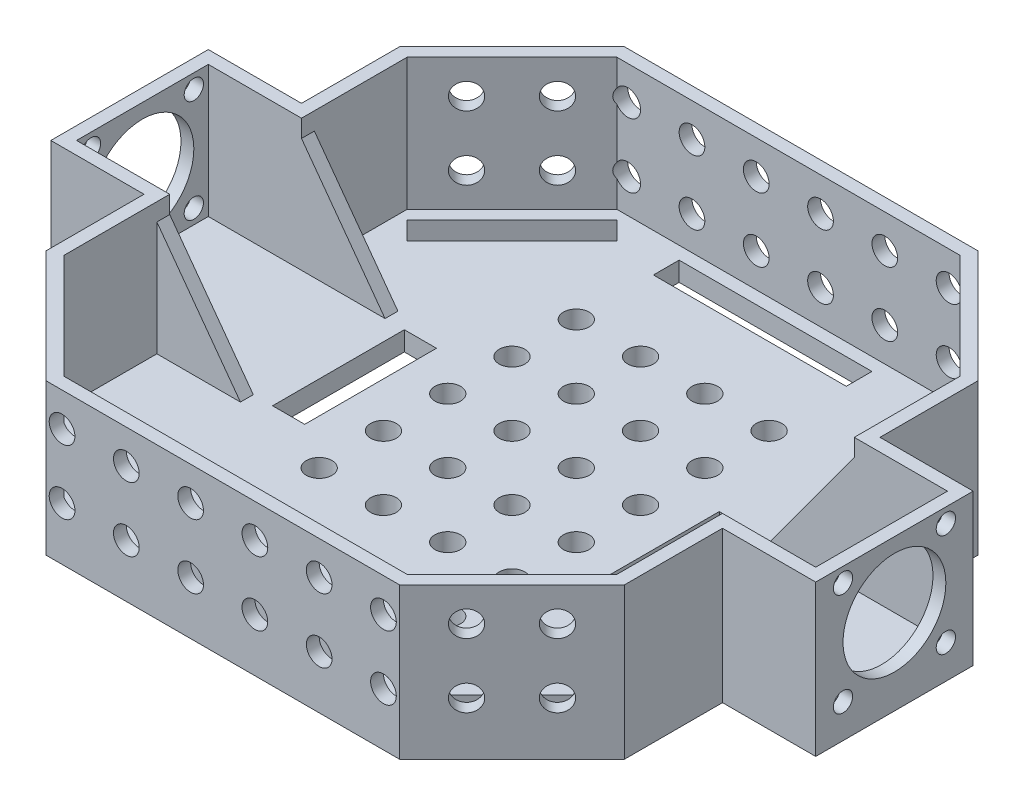
SolidWorks part; units mm, degrees
ref_plane "Front Plane" through (0, 0, 0) normal (0, 0, 1) x (1, 0, 0)
ref_plane "Top Plane" through (0, 0, 0) normal (0, 1, 0) x (1, 0, 0)
ref_plane "Right Plane" through (0, 0, 0) normal (1, 0, 0) x (0, 0, -1)
sketch "Sketch1" plane through (0, 0, 0) normal (0, 1, 0) x (1, 0, 0)
  line L1 (0, 0) -> (90, 0)
  line L2 (0, 0) -> (0, 90)
  line L3 (0, 90) -> (90, 90)
  line L4 (90, 0) -> (90, 90)
  dimension "D1" = 90
extrude "Boss-Extrude1" add sketch "Sketch1" along normal blind 3
sketch "Sketch2" plane through (0, 3, 0) normal (0, 1, 0) x (1, 0, 0)
  line L0 (0, 90) -> (0, 0) construction
  line L1 (0, 34.75) -> (-14.5, 34.75)
  line L2 (0, 34.75) -> (0, 55.25)
  line L3 (0, 55.25) -> (-14.5, 55.25)
  line L4 (-14.5, 34.75) -> (-14.5, 55.25)
  line L5 (90, 0) -> (90, 90) construction
  line L6 (90, 34.75) -> (104.5, 34.75)
  line L7 (90, 34.75) -> (90, 55.25)
  line L8 (90, 55.25) -> (104.5, 55.25)
  line L9 (104.5, 34.75) -> (104.5, 55.25)
  line L10 (-14.5, 55.25) -> (17.5, 55.25) construction
  line L11 (104.5, 55.25) -> (72.5, 55.25) construction
  point P12 (97.9626, 54.4694)
  point P13 (90, 45)
  point P14 (90, 45)
  point P15 (0, 45)
  point P16 (0, 45)
  dimension "D1" = 32
  dimension "D2" = 55
  dimension "D3" = 20.5
extrude "Boss-Extrude2" add sketch "Sketch2" against normal up to surface (3 mm away) up to face at (45, 0, -45)
sketch "Sketch3" plane through (0, 3, 0) normal (0, 1, 0) x (1, 0, 0)
  line L0 (-14.5, 34.75) -> (0, 34.75) construction
  line L1 (-14.5, 55.25) -> (-12.5, 55.25)
  line L2 (-14.5, 55.25) -> (-14.5, 34.75)
  line L3 (-14.5, 34.75) -> (-12.5, 34.75)
  line L4 (-12.5, 55.25) -> (-12.5, 34.75)
  line L5 (104.5, 55.25) -> (90, 55.25) construction
  line L6 (104.5, 34.75) -> (102.5, 34.75)
  line L7 (104.5, 34.75) -> (104.5, 55.25)
  line L8 (104.5, 55.25) -> (102.5, 55.25)
  line L9 (102.5, 34.75) -> (102.5, 55.25)
  dimension "D1" = 2
extrude "Boss-Extrude3" add sketch "Sketch3" along normal blind 20.5
sketch "Sketch4" plane through (-12.5, 0, 0) normal (1, 0, 0) x (0, 0, -1)
  line L0 (34.75, 3.25) -> (55.25, 3.25) construction
  line L1 (34.75, 23.5) -> (34.75, 3) construction
  line L2 (55.25, 23.5) -> (55.25, 3) construction
  line L3 (34.75, 3) -> (55.25, 3) construction
  line L5 (34.75, 23.5) -> (55.25, 23.5) construction
  line L6 (37, 5.25) -> (53, 5.25) construction
  line L7 (53, 5.25) -> (53, 21.25) construction
  circle A0 centre (45, 13.25) radius 8
  circle A1 centre (53, 21.25) radius 1.5
  circle A2 centre (53, 5.25) radius 1.5
  circle A3 centre (37, 21.25) radius 1.5
  circle A4 centre (37, 5.25) radius 1.5
  point P13 (45, 23.5)
  point P21 (53, 13.25)
  point P22 (48.4513, 5.25)
  point P23 (45, 5.25)
  point P24 (45, 3.25)
  point P25 (37, 5.25)
  dimension "D2" = 16
  dimension "D7" = 3
  dimension "D1" = 0.25
  dimension "D3" = 10
  dimension "D4" = 16
  dimension "D5" = 16
  dimension "D6" = 10
extrude "Cut-Extrude1" cut sketch "Sketch4" against normal through all both and the other way through all
sketch "Sketch5" plane through (0, 3, 0) normal (0, 1, 0) x (1, 0, 0)
  line L0 (-14.5, 55.25) -> (-14.5, 34.75) construction
  line L1 (2, 34.75) -> (-14.5, 34.75)
  line L2 (2, 34.75) -> (2, 32.75)
  line L3 (2, 32.75) -> (-14.5, 32.75)
  line L4 (-14.5, 34.75) -> (-14.5, 32.75)
  line L5 (-12.5, 45) -> (104.5, 45) construction
  line L6 (-12.5, 34.75) -> (-12.5, 55.25) construction
  line L7 (104.5, 34.75) -> (104.5, 55.25) construction
  line L8 (104.5, 34.75) -> (104.5, 55.25)
  line L9 (45, 0) -> (45, 90) construction
  line L10 (0, 0) -> (90, 0) construction
  line L11 (90, 90) -> (0, 90) construction
  line L12 (2, 57.25) -> (-14.5, 57.25)
  line L13 (-14.5, 55.25) -> (-14.5, 57.25)
  line L14 (2, 55.25) -> (-14.5, 55.25)
  line L15 (2, 55.25) -> (2, 57.25)
  line L16 (88, 32.75) -> (104.5, 32.75)
  line L17 (104.5, 34.75) -> (104.5, 32.75)
  line L18 (88, 34.75) -> (104.5, 34.75)
  line L19 (88, 34.75) -> (88, 32.75)
  line L20 (88, 55.25) -> (88, 57.25)
  line L21 (88, 55.25) -> (104.5, 55.25)
  line L22 (104.5, 55.25) -> (104.5, 57.25)
  line L23 (88, 57.25) -> (104.5, 57.25)
  line L24 (-12.5, 34.75) -> (0, 34.75) construction
  point P4 (2.0114, 34.6763)
  point P31 (0, 34.75)
  point P32 (0, 0)
  point P33 (86.9296, 57.25)
  dimension "D1" = 2
  dimension "D2" = 2
extrude "Boss-Extrude4" add sketch "Sketch5" against normal up to surface and the other way up to surface contours L12 L13 L14 L15 | L2 L1 L4 L3 | L20 L23 L22 L21 | L16 L17 L18 L19 up to face at (45, 0, -45) other way up to face at (103.5, 23.5, -45)
sketch "Sketch6" plane through (0, 0, -57.25) normal (0, 0, -1) x (-1, 0, 0)
  line L0 (-90, 23.5) -> (-75, 3)
  line L2 (-75, 3) -> (-90, 3)
  line L3 (-90, 3) -> (-90, 23.5)
  line L4 (0, 23.5) -> (-15, 3)
  line L5 (-15, 3) -> (0, 3)
  line L6 (0, 3) -> (0, 23.5)
  line L7 (-88, 23.5) -> (-104.5, 23.5) construction
  line L8 (-2, 23.5) -> (14.5, 23.5) construction
  point P3 (-20.5, 3)
  point P4 (-69.5, 3)
  point P10 (-20.5, 3)
  point P13 (-20.5, 3)
  point P14 (-69.5, 3)
  point P15 (-10.2777, 3)
  point P16 (-67.4871, 3)
  point P17 (-74.1327, 3)
  point P18 (-90, 23.5)
  point P21 (0, 23.5)
  dimension "D1" = 15
extrude "Boss-Extrude5" add sketch "Sketch6" against normal up to surface (24.5 mm away) up to face at (94.1667, 8.8333, -32.75)
sketch "Sketch7" plane through (0, 3, 0) normal (0, 1, 0) x (1, 0, 0)
  line L1 (102.5, 34.75) -> (-12.5, 34.75)
  line L2 (102.5, 34.75) -> (102.5, 55.25)
  line L3 (102.5, 55.25) -> (-12.5, 55.25)
  line L4 (-12.5, 34.75) -> (-12.5, 55.25)
extrude "Cut-Extrude2" cut sketch "Sketch7" along normal through all
sketch "Sketch8" plane through (0, 3, 0) normal (0, 1, 0) x (1, 0, 0)
  line L0 (15, 55.25) -> (-12.5, 55.25) construction
  line L1 (18, 55.25) -> (23, 55.25)
  line L2 (18, 55.25) -> (18, 34.75)
  line L3 (18, 34.75) -> (23, 34.75)
  line L4 (23, 55.25) -> (23, 34.75)
  line L5 (67, 55.25) -> (72, 55.25)
  line L6 (67, 55.25) -> (67, 34.75)
  line L7 (67, 34.75) -> (72, 34.75)
  line L8 (72, 55.25) -> (72, 34.75)
  line L9 (-12.5, 34.75) -> (15, 34.75) construction
  line L10 (18, 55.25) -> (15, 55.25) construction
  line L11 (72, 55.25) -> (75, 55.25) construction
  line L12 (-12.5, 34.75) -> (-12.5, 55.25) construction
  dimension "D1" = 30.5
  dimension "D2" = 5
extrude "Cut-Extrude3" cut sketch "Sketch8" against normal through all
sketch "Sketch9" plane through (0, 0, 0) normal (0, -1, 0) x (1, 0, 0)
  line L0 (17.5, 0) -> (0, -17.5)
  line L1 (0, 0) -> (90, 0) construction
  line L2 (0, -32.75) -> (0, 0) construction
  line L3 (0, -17.5) -> (0, 0)
  line L4 (0, 0) -> (17.5, 0)
  line L5 (45, 0) -> (45, -90) construction
  line L6 (90, -90) -> (0, -90) construction
  line L7 (0, -72.5) -> (17.5, -90)
  line L8 (0, -90) -> (0, -57.25) construction
  line L9 (17.5, -90) -> (0, -90)
  line L10 (0, -90) -> (0, -72.5)
  line L11 (72.5, -90) -> (90, -90)
  line L12 (90, -72.5) -> (72.5, -90)
  line L13 (90, -90) -> (90, -72.5)
  line L14 (90, -17.5) -> (90, 0)
  line L15 (72.5, 0) -> (90, -17.5)
  line L16 (90, 0) -> (72.5, 0)
  point P16 (16.3771, 0)
  point P19 (0, -12.7712)
  dimension "D1" = 17.5
extrude "Cut-Extrude4" cut sketch "Sketch9" against normal through all
sketch "Sketch10" plane through (0, 3, 0) normal (0, 1, 0) x (1, 0, 0)
  line L0 (88, 32.75) -> (88, 18.3284)
  line L1 (90, 32.75) -> (75, 32.75) construction
  line L2 (88, 18.3284) -> (71.6716, 2)
  line L3 (71.6716, 2) -> (18.3284, 2)
  line L4 (18.3284, 2) -> (2, 18.3284)
  line L5 (2, 18.3284) -> (2, 32.75)
  line L6 (15, 32.75) -> (0, 32.75) construction
  line L7 (2, 32.75) -> (0, 32.75)
  line L8 (0, 32.75) -> (0, 17.5)
  line L9 (0, 17.5) -> (17.5, 0)
  line L10 (17.5, 0) -> (72.5, 0)
  line L11 (72.5, 0) -> (90, 17.5)
  line L12 (90, 17.5) -> (90, 32.75)
  line L13 (90, 32.75) -> (88, 32.75)
  line L14 (90, 57.25) -> (90, 72.5)
  line L15 (90, 72.5) -> (72.5, 90)
  line L16 (72.5, 90) -> (17.5, 90)
  line L17 (17.5, 90) -> (0, 72.5)
  line L18 (0, 72.5) -> (0, 57.25)
  line L22 (2, 57.25) -> (2, 71.6716)
  line L23 (2, 71.6716) -> (18.3284, 88)
  line L24 (18.3284, 88) -> (71.6716, 88)
  line L25 (71.6716, 88) -> (88, 71.6716)
  line L26 (88, 71.6716) -> (88, 57.25)
  line L27 (90, 57.25) -> (75, 57.25) construction
  line L28 (88, 57.25) -> (90, 57.25)
  line L29 (88, 71.6716) -> (90, 71.6716) construction
  line L30 (74.5732, 85.0984) -> (75.9874, 86.5126) construction
  line L31 (55.78, 88) -> (55.78, 90) construction
  line L32 (14.4935, 84.165) -> (13.0792, 85.5792) construction
  line L33 (2, 68.1739) -> (0, 68.1739) construction
  line L34 (0, 57.25) -> (2, 57.25)
  line L35 (15, 57.25) -> (0, 57.25) construction
  line L36 (4.0958, 16.2326) -> (2.6816, 14.8184) construction
  line L37 (26.8759, 2) -> (26.8759, 0) construction
  line L38 (76.1039, 6.4323) -> (77.5181, 5.0181) construction
  point P60 (4.7561, 57.25)
  dimension "D1" = 2
extrude "Boss-Extrude6" add sketch "Sketch10" along normal up to surface (20.5 mm away)
sketch "Sketch11" plane through (0, 0, 0) normal (0, 0, 1) x (1, 0, 0)
  line L0 (70, 8.25) -> (70, 3) construction
  line L2 (70, 8.25) -> (72.5, 8.25) construction
  line L3 (72.5, 23.5) -> (72.5, 0) construction
  line L4 (71.6716, 3) -> (18.3284, 3) construction
  line L5 (20, 18.25) -> (20, 23.5) construction
  line L6 (17.5, 23.5) -> (72.5, 23.5) construction
  line L7 (20, 18.25) -> (17.5, 18.25) construction
  line L8 (17.5, 23.5) -> (17.5, 0) construction
  line L9 (71.6716, 3) -> (18.3284, 3)
  circle A0 centre (70, 8.25) radius 2
  circle A1 centre (60, 8.25) radius 2
  circle A2 centre (50, 8.25) radius 2
  circle A3 centre (40, 8.25) radius 2
  circle A4 centre (30, 8.25) radius 2
  circle A5 centre (20, 8.25) radius 2
  circle A6 centre (60, 18.25) radius 2
  circle A7 centre (50, 18.25) radius 2
  circle A8 centre (40, 18.25) radius 2
  circle A9 centre (30, 18.25) radius 2
  circle A10 centre (20, 18.25) radius 2
  circle A11 centre (70, 18.25) radius 2
  point P2 (30.5798, 19.5)
  point P5 (30.5382, 19.5)
  point P6 (23.0178, 19.5)
  dimension "D4" = 4
  dimension "D3" = 10
  dimension "D5" = 10
  dimension "D1" = 6
  dimension "D2" = 2
extrude "Cut-Extrude5" cut sketch "Sketch11" against normal through all contours A10 | A4 | A9 | A8 | A7 | A6 | A11 | A3 | A5 | A0 | A1 | A2
sketch "Sketch12" plane through (8.75, 0, -8.75) normal (-0.7071, 0, 0.7071) x (0.7071, 0, 0.7071)
  line L0 (-5, 18.25) -> (5, 18.25) construction
  line L1 (-12.3744, 23.5) -> (12.3744, 23.5) construction
  circle A0 centre (-5, 18.25) radius 2
  circle A1 centre (5, 18.25) radius 2
  circle A2 centre (5, 8.25) radius 2
  circle A3 centre (-5, 8.25) radius 2
  ellipse E0 centre (14.1421, 18.25) end of major axis (14.1421, 16.25) minor radius 1.4142 construction
  ellipse E1 centre (14.1421, 8.25) end of major axis (14.1421, 6.25) minor radius 1.4142 construction
  ellipse E2 centre (14.1421, 18.25) end of major axis (14.1421, 16.25) minor radius 1.4142
  ellipse E3 centre (14.1421, 8.25) end of major axis (14.1421, 6.25) minor radius 1.4142
  point P30 (0, 18.25)
  point P33 (0, 23.5)
  dimension "D2" = 4
  dimension "D1" = 10
extrude "Cut-Extrude6" cut sketch "Sketch12" against normal through all contours A1 | A0 | A3 | A2
sketch "Sketch13" plane through (-36.25, 0, -36.25) normal (-0.7071, 0, -0.7071) x (-0.7071, 0, 0.7071)
  line L0 (-68.6396, 8.25) -> (-58.6396, 8.25) construction
  line L1 (-76.014, 0) -> (-51.2652, 0) construction
  circle A0 centre (-68.6396, 18.25) radius 2
  circle A1 centre (-58.6396, 18.25) radius 2
  circle A2 centre (-58.6396, 8.25) radius 2
  circle A3 centre (-68.6396, 8.25) radius 2
  ellipse E0 centre (-77.7817, 8.25) end of major axis (-77.7817, 6.25) minor radius 1.4142 construction
  ellipse E1 centre (-77.7817, 18.25) end of major axis (-77.7817, 16.25) minor radius 1.4142 construction
  ellipse E2 centre (-77.7817, 8.25) end of major axis (-77.7817, 6.25) minor radius 1.4142
  ellipse E3 centre (-77.7817, 18.25) end of major axis (-77.7817, 16.25) minor radius 1.4142
  point P30 (-60.7953, 7.25)
  point P31 (-59.1842, 7.25)
  point P32 (-63.6396, 8.25)
  point P35 (-63.6396, 0)
  dimension "D2" = 4
  dimension "D1" = 10
extrude "Cut-Extrude7" cut sketch "Sketch13" against normal through all contours A0 | A2 | A1 | A3
sketch "Sketch14" plane through (0, 3, 0) normal (0, 1, 0) x (1, 0, 0)
  line L0 (23, 45) -> (67, 45) construction
  line L1 (23, 34.75) -> (23, 55.25) construction
  line L2 (67, 55.25) -> (67, 34.75) construction
  line L3 (86.5858, 19.7426) -> (70.2574, 3.4142)
  line L4 (60, 8) -> (30, 8)
  line L5 (60, 8) -> (60, 4)
  line L6 (60, 4) -> (30, 4)
  line L7 (45, 8) -> (45, 4)
  line L8 (70.2574, 3.4142) -> (67.4289, 6.2426)
  line L9 (67.4289, 6.2426) -> (83.7574, 22.5711)
  line L10 (83.7574, 22.5711) -> (86.5858, 19.7426)
  line L11 (45, 45) -> (45, 2) construction
  line L12 (71.6716, 2) -> (18.3284, 2) construction
  line L13 (50, 40) -> (60, 40) construction
  line L14 (50, 40) -> (50, 30) construction
  line L15 (70.2574, 3.4142) -> (71.6716, 2) construction
  line L16 (60, 4) -> (60, 2) construction
  line L17 (88, 18.3284) -> (71.6716, 2) construction
  line L18 (52, 2) -> (48, 2) construction
  line L19 (52, 2) -> (48, 2)
  line L20 (62, 20) -> (58, 20) construction
  line L21 (22.5711, 6.2426) -> (6.2426, 22.5711)
  line L22 (19.7426, 3.4142) -> (22.5711, 6.2426)
  line L23 (3.4142, 19.7426) -> (19.7426, 3.4142)
  line L24 (6.2426, 22.5711) -> (3.4142, 19.7426)
  line L25 (30, 8) -> (30, 4)
  line L26 (60, 82) -> (60, 86)
  line L27 (45, 82) -> (45, 86)
  line L28 (60, 82) -> (30, 82)
  line L29 (60, 86) -> (30, 86)
  line L30 (30, 82) -> (30, 86)
  line L31 (6.2426, 67.4289) -> (3.4142, 70.2574)
  line L32 (22.5711, 83.7574) -> (6.2426, 67.4289)
  line L33 (3.4142, 70.2574) -> (19.7426, 86.5858)
  line L34 (19.7426, 86.5858) -> (22.5711, 83.7574)
  line L35 (83.7574, 67.4289) -> (86.5858, 70.2574)
  line L36 (67.4289, 83.7574) -> (83.7574, 67.4289)
  line L37 (70.2574, 86.5858) -> (67.4289, 83.7574)
  line L38 (86.5858, 70.2574) -> (70.2574, 86.5858)
  circle A0 centre (50, 40) radius 2
  circle A1 centre (60, 40) radius 2
  circle A2 centre (60, 30) radius 2
  circle A3 centre (60, 20) radius 2
  circle A4 centre (50, 30) radius 2
  circle A5 centre (50, 20) radius 2
  circle A6 centre (30, 20) radius 2
  circle A7 centre (40, 20) radius 2
  circle A8 centre (40, 30) radius 2
  circle A9 centre (30, 30) radius 2
  circle A10 centre (30, 40) radius 2
  circle A11 centre (40, 40) radius 2
  circle A12 centre (30, 50) radius 2
  circle A13 centre (40, 50) radius 2
  circle A14 centre (30, 60) radius 2
  circle A15 centre (40, 60) radius 2
  circle A16 centre (30, 70) radius 2
  circle A17 centre (40, 70) radius 2
  circle A18 centre (60, 50) radius 2
  circle A19 centre (50, 50) radius 2
  circle A20 centre (50, 60) radius 2
  circle A21 centre (50, 70) radius 2
  circle A22 centre (60, 70) radius 2
  circle A23 centre (60, 60) radius 2
  dimension "D1" = 4
  dimension "D4" = 10
  dimension "D5" = 10
  dimension "D6" = 5
  dimension "D7" = 5
  dimension "D8" = 2
  dimension "D9" = 15
  dimension "D2" = 2
  dimension "D3" = 3
extrude "Cut-Extrude8" cut sketch "Sketch14" against normal through all contours A22 | L26 L29 L27 L28 | L30 L28 L27 L29 | A17 | A21 | A20 | A18 | A0 | A4 | A2 | A3 | A5 | A7 | A11 | A9 | A6 | L4 L25 L6 L7 | L4 L7 L6 L5 | L10 L9 L8 L3 | L35 L38 L37 L36 | L34 L33 L31 L32 | L21 L24 L23 L22 | A13 | A15 | A14 | A16 | A23 | A19 | A1 | A8 | A10 | A12
